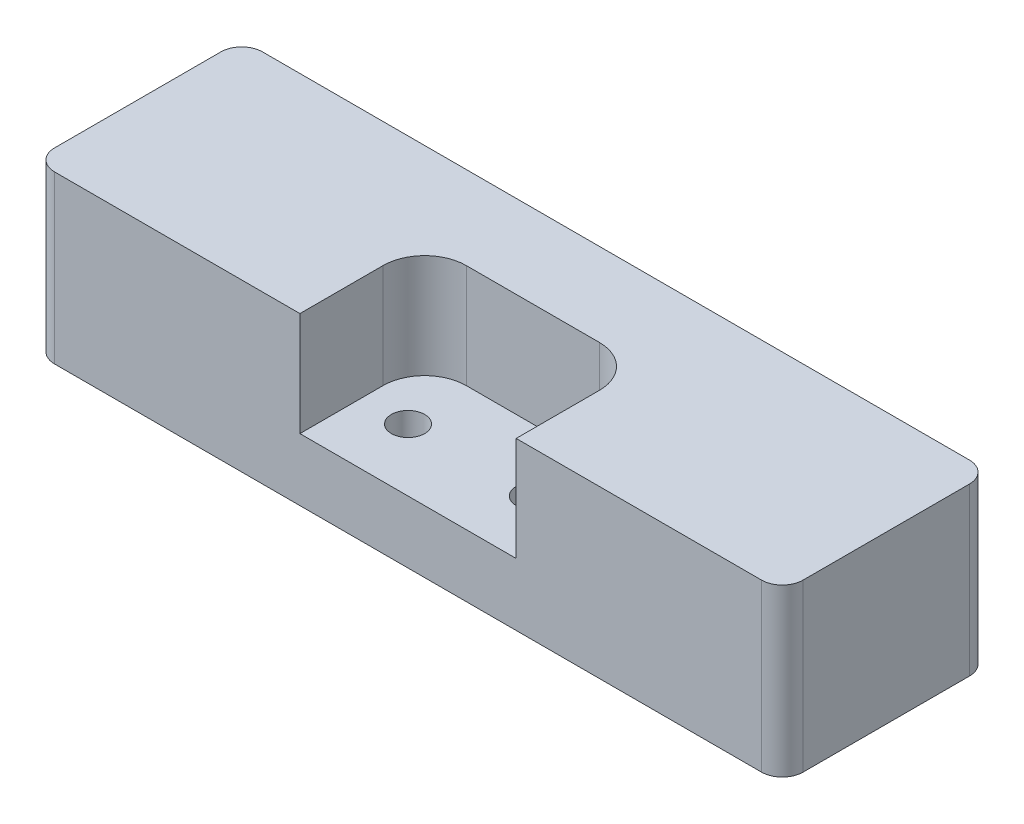
SolidWorks part; units mm, degrees
material "Liga 1060"
ref_plane "Plano frontal" through (0, 0, 0) normal (0, 0, 1) x (1, 0, 0)
ref_plane "Plano superior" through (0, 0, 0) normal (0, 1, 0) x (1, 0, 0)
ref_plane "Plano direito" through (0, 0, 0) normal (1, 0, 0) x (0, 0, -1)
sketch "Esboço2" plane through (0, 0, 0) normal (0, 1, 0) x (1, 0, 0)
  line L7 (33, 0) -> (-3, 0)
  line L8 (-3, 10) -> (33, 10)
  line L9 (33, 0) -> (33, 10)
  line L10 (-3, 0) -> (-3, 10)
  point P2 (15, 10)
  point P6 (15, 0)
  point P7 (33, 10)
  point P13 (0, 0)
  point P18 (-3, 10)
  dimension "D2" = 10
  dimension "D3" = 36
  dimension "D1" = 36
extrude "Ressalto-extrusão2" add sketch "Esboço2" along normal blind 8
sketch "Esboço4" plane through (0, 8, 0) normal (0, 1, 0) x (1, 0, 0)
  line L0 (15, 0) -> (15, 2.6) construction
  line L1 (-3, 0) -> (33, 0) construction
  line L2 (6.5, 2.6) -> (23.5, 2.6) construction
  line L4 (20.9, 0) -> (26.1, 0)
  line L5 (20.9, 0) -> (20.9, 5.2)
  line L6 (20.9, 5.2) -> (26.1, 5.2)
  line L7 (26.1, 0) -> (26.1, 5.2)
  line L8 (20.9, 0) -> (26.1, 5.2) construction
  line L9 (20.9, 5.2) -> (26.1, 0) construction
  line L10 (9.1, 0) -> (3.9, 0)
  line L11 (9.1, 0) -> (9.1, 5.2)
  line L12 (9.1, 5.2) -> (3.9, 5.2)
  line L13 (3.9, 0) -> (3.9, 5.2)
  line L14 (9.1, 0) -> (3.9, 5.2) construction
  line L15 (9.1, 5.2) -> (3.9, 0) construction
  point P7 (15, 2.6)
  dimension "D1" = 17
  dimension "D2" = 2.6
  dimension "D3" = 5.2
  dimension "D4" = 5.2
sketch "Esboço5" plane through (0, 8, 0) normal (0, 1, 0) x (1, 0, 0)
  line L0 (15, 0) -> (15, 6) construction
  line L1 (-3, 0) -> (33, 0) construction
  line L2 (9.8, 6) -> (20.2, 6)
  line L3 (9.8, 6) -> (9.8, 0)
  line L4 (9.8, 0) -> (20.2, 0)
  line L5 (20.2, 0) -> (20.2, 6)
  point P7 (15, 6)
  dimension "D1" = 10.4
  dimension "D2" = 6
sketch "Esboço6" plane through (0, 0, 0) normal (0, 0, 1) x (1, 0, 0)
  line L0 (15, 0) -> (15, 8) construction
  line L1 (-3, 0) -> (33, 0) construction
  line L2 (9.8, 8) -> (20.2, 8) construction
  line L3 (-3, 3) -> (9.8, 3) construction
  line L4 (-3, 8) -> (-3, 0) construction
  line L5 (33, 8) -> (33, 0) construction
  line L7 (15, 3) -> (20.2, 3)
  line L8 (15, 3) -> (9.8, 3)
  line L9 (9.8, 3) -> (9.8, 8)
  line L10 (20.2, 3) -> (33, 3) construction
  line L11 (-3, 8) -> (33, 8) construction
  line L12 (9.8, 8) -> (20.2, 8)
  line L13 (20.2, 8) -> (20.2, 3)
  dimension "D2" = 5.2
  dimension "D1" = 3
sketch "Esboço7" plane through (0, 0, -10) normal (0, 0, -1) x (-1, 0, 0)
  line L0 (3, 3) -> (-33, 3) construction
  line L1 (3, 8) -> (3, 0) construction
  line L2 (-33, 8) -> (-33, 0) construction
  line L3 (-33, 0) -> (3, 0) construction
  line L4 (-15, 8) -> (-15, 0) construction
  line L5 (-33, 8) -> (3, 8) construction
  line L6 (-10, 3) -> (-20, 3) construction
  line L7 (-12.5, 0) -> (-12.5, 8) construction
  line L8 (3, 4.5) -> (-33, 4.5) construction
  arc A0 (-10, 3) -> (-20, 3) centre (-15, 3) ccw
  circle A1 centre (-12.5, 4.5) radius 1
  circle A3 centre (-17.5, 4.5) radius 1
  point P19 (-12.5, 4.5)
  dimension "D2" = 2.5
  dimension "D1" = 3
  dimension "D3" = 1.5
fillet "Filete3" radius 1 4 edges at (33, 4, 0) (33, 4, -10) (-3, 4, -10) (-3, 4, 0)
extrude "Corte-extrusão1" cut sketch "Esboço5" against normal blind 5
fillet "Filete4" radius 2 2 edges at (20.2, 5.5, -6) (9.8, 5.5, -6)
sketch "Esboço8" plane through (0, 3, 0) normal (0, 1, 0) x (1, 0, 0)
  line L0 (15, 0) -> (15, 3) construction
  line L1 (9.8, 0) -> (20.2, 0) construction
  line L2 (12, 3) -> (18, 3)
  line L3 (18.2, 6) -> (11.8, 6) construction
  point P7 (15, 3)
  dimension "D1" = 6
  dimension "D2" = 3
hole_wizard "Broca de rosquear para tarraxa de M2x0.41" positions "3DSketch1" profile "Esboço9" hole size "M2x0.4" standard "Ansi Metric" end condition through all
sketch3d "3DSketch1"
  point P0 (12, 3, -3)
  point P3 (18, 3, -3)
sketch "Esboço9" plane through (12, 3, -3) normal (1, 0, 0) x (0, 0, 1)
  line L0 (0, 0) -> (0, 3)
  line L1 (0, 3) -> (0.8, 3)
  line L2 (0.8, 3) -> (0.8, 0)
  line L5 (0.8, 0) -> (0, 0)
  line L11 (0, -6.35) -> (0, 107.95) construction
  dimension "Thru Hole Dia." = 1.6
  dimension "Thru Hole Depth" = 3
